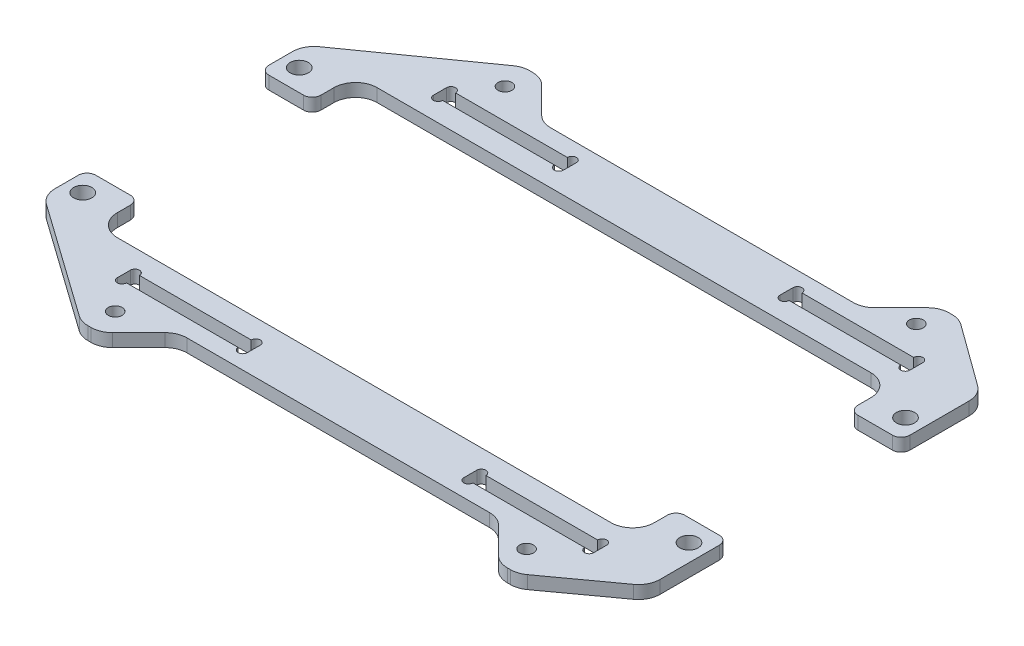
SolidWorks part; units mm, degrees
material "玻纤"
ref_plane "前视基准面" through (0, 0, 0) normal (0, 0, 1) x (1, 0, 0)
ref_plane "上视基准面" through (0, 0, 0) normal (0, 1, 0) x (1, 0, 0)
ref_plane "右视基准面" through (0, 0, 0) normal (1, 0, 0) x (0, 0, -1)
sketch "草图1" plane through (0, 0, 0) normal (0, 1, 0) x (1, 0, 0)
  line L1 (-80, -60) -> (80, -60)
  line L2 (-80, -60) -> (-80, 60)
  line L3 (-80, 60) -> (80, 60)
  line L4 (80, -60) -> (80, 60)
  line L5 (-80, -60) -> (80, 60) construction
  line L6 (-80, 60) -> (80, -60) construction
  point P0 (0, 0)
  dimension "D1" = 160
  dimension "D2" = 120
extrude "凸台-拉伸1" add sketch "草图1" along normal blind 3
sketch "草图2" plane through (0, 3, 0) normal (0, 1, 0) x (1, 0, 0)
  line L1 (-48.5, -45) -> (46.5, -45) construction
  line L2 (-48.5, -45) -> (-48.5, 45) construction
  line L3 (-48.5, 45) -> (46.5, 45) construction
  line L4 (46.5, -45) -> (46.5, 45) construction
  line L5 (-48.5, -45) -> (46.5, 45) construction
  line L6 (-48.5, 45) -> (46.5, -45) construction
  circle A0 centre (-48.5, 45) radius 1.6
  circle A1 centre (-48.5, -45) radius 1.6
  circle A2 centre (46.5, -45) radius 1.6
  circle A3 centre (46.5, 45) radius 1.6
  point P0 (-1, 0)
  dimension "D3" = 3.2
  dimension "D1" = 90
  dimension "D2" = 95
  dimension "D4" = 1
extrude "切除-拉伸1" cut sketch "草图2" against normal blind 3
sketch "草图3" plane through (0, 3, 0) normal (0, 1, 0) x (1, 0, 0)
  line L0 (80, -60) -> (80, 60) construction
  line L1 (-80, -30) -> (80, -30)
  line L2 (-80, -30) -> (-80, 30)
  line L3 (-80, 30) -> (80, 30)
  line L4 (80, -30) -> (80, 30)
  line L5 (-80, -30) -> (80, 30) construction
  line L6 (-80, 30) -> (80, -30) construction
  line L7 (-80, 30) -> (-44.2474, 60)
  line L8 (80, 60) -> (-80, 60) construction
  line L9 (-44.2474, 60) -> (44.2474, 60)
  line L10 (44.2474, 60) -> (80, 30)
  line L11 (80, -30) -> (44.2474, -60)
  line L12 (-80, -60) -> (80, -60) construction
  line L13 (44.2474, -60) -> (-44.2474, -60)
  line L14 (-44.2474, -60) -> (-80, -30)
  point P0 (0, 0)
  line M11 (80, -60) -> (80, 60)
  line M12 (80, 60) -> (-80, 60)
  line M13 (-80, 60) -> (-80, -60)
  line M14 (-80, -60) -> (80, -60)
  dimension "D1" = 60
  dimension "D2" = 40
  dimension "D3" = 40
extrude "切除-拉伸2" cut sketch "草图3" against normal blind 3 contours L7 M13 M12 | L10 M12 M11 | L11 M11 M14 | L14 M14 M13
sketch "草图14" plane through (0, 3, 0) normal (0, 1, 0) x (1, 0, 0)
  line L0 (44.2474, 60) -> (80, 30) construction
  line L1 (68, 40.0692) -> (80, 40.0692)
  line L2 (68, 40.0692) -> (68, -40.0692)
  line L3 (68, -40.0692) -> (80, -40.0692)
  line L4 (80, 40.0692) -> (80, -40.0692)
  line L5 (80, -30) -> (44.2474, -60) construction
  dimension "D1" = 12
extrude "切除-拉伸13" cut sketch "草图14" against normal through all
sketch "草图4" plane through (0, 3, 0) normal (0, 1, 0) x (1, 0, 0)
  line L0 (-76, -30) -> (-76, 30) construction
  line L1 (-80, 30) -> (-72, 30) construction
  line L2 (-80, 30) -> (-80, -30) construction
  line L3 (-80, -30) -> (-72, -30) construction
  line L4 (-72, 30) -> (-72, -30) construction
  line L5 (0, -60) -> (0, 60) construction
  line L6 (-44.2474, -60) -> (44.2474, -60) construction
  line L7 (44.2474, 60) -> (-44.2474, 60) construction
  line L8 (-76, 25) -> (64, 25) construction
  line L9 (64, 25) -> (64, -25) construction
  line L10 (-76, -25) -> (64, -25) construction
  line L11 (68, 40.0692) -> (68, -40.0692) construction
  line L13 (64, 0) -> (-76, 0) construction
  circle A0 centre (-76, 25) radius 2.1
  circle A1 centre (-76, -25) radius 2.1
  circle A2 centre (-76, 0) radius 2.1
  circle A8 centre (64, 25) radius 2.1
  circle A9 centre (64, -25) radius 2.1
  circle A11 centre (64, 0) radius 2.1
  point P15 (-76, 0)
  dimension "D3" = 5
  dimension "D5" = 5
  dimension "D6" = 4.2
  dimension "D8" = 4.2
  dimension "D1" = 8
  dimension "D7" = 4
extrude "切除-拉伸3" cut sketch "草图4" against normal blind 8
sketch "草图5" plane through (0, 3, 0) normal (0, 1, 0) x (1, 0, 0)
  line L0 (-44.2474, -60) -> (44.2474, -60) construction
  line L1 (-80, 35) -> (68, 35) construction
  line L2 (-80, 35) -> (-80, -35) construction
  line L3 (-80, -35) -> (68, -35) construction
  line L5 (-55, 35) -> (-25, 35)
  line L6 (-55, 35) -> (-55, 38)
  line L7 (-55, 38) -> (-25, 38)
  line L8 (-25, 35) -> (-25, 38)
  line L9 (25, 35) -> (55, 35)
  line L10 (25, 35) -> (25, 38)
  line L11 (25, 38) -> (55, 38)
  line L12 (55, 35) -> (55, 38)
  line L13 (-55, -35) -> (-25, -35)
  line L14 (-55, -35) -> (-55, -38)
  line L15 (-55, -38) -> (-25, -38)
  line L16 (-25, -35) -> (-25, -38)
  line L17 (25, -35) -> (55, -35)
  line L18 (25, -35) -> (25, -38)
  line L19 (25, -38) -> (55, -38)
  line L20 (55, -35) -> (55, -38)
  line L21 (44.2474, 60) -> (-44.2474, 60) construction
  line L23 (68, 40.0692) -> (68, -40.0692) construction
  dimension "D1" = 3
  dimension "D2" = 3
  dimension "D3" = 3
  dimension "D4" = 3
  dimension "D5" = 25
  dimension "D6" = 30
  dimension "D7" = 30
  dimension "D8" = 13
  dimension "D10" = 30
  dimension "D11" = 30
  dimension "D12" = 25
  dimension "D13" = 25
  dimension "D15" = 25
extrude "切除-拉伸4" cut sketch "草图5" against normal blind 8
sketch "草图7" plane through (0, 3, 0) normal (0, 1, 0) x (1, 0, 0)
  line L0 (-80, -30) -> (-50.4129, -51)
  line L1 (-50.4129, -51) -> (-46.0147, -51)
  line L2 (-46.0147, -51) -> (-37.0147, -42)
  line L3 (-37.0147, -42) -> (37.0147, -42)
  line L4 (0, 60) -> (0, -60) construction
  line L5 (44.2474, 60) -> (-44.2474, 60) construction
  line L6 (-80, 0) -> (68, 0) construction
  line L7 (-80, 30) -> (-80, -30) construction
  line L8 (-44.2474, -60) -> (44.2474, -60) construction
  line L14 (-67, -29) -> (67, 29) construction
  line L15 (-67, 29) -> (67, -29) construction
  line L21 (-55, -38) -> (-25, -38) construction
  line L22 (68, -40.0692) -> (44.2474, -60) construction
  line L23 (-44.2474, -60) -> (-80, -30) construction
  line L24 (68, -40.0692) -> (44.2474, -60)
  line L25 (68, 40.0692) -> (68, -40.0692) construction
  line L29 (-44.2474, -60) -> (44.2474, -60)
  line L30 (-44.2474, -60) -> (-80, -30)
  line L31 (46.0147, -51) -> (37.0147, -42)
  line L32 (50.4129, -51) -> (46.0147, -51)
  line L34 (68, -38.2242) -> (50.4129, -51)
  line L35 (68, -40.0692) -> (68, -38.2242)
  line L36 (68, 40.0692) -> (68, 38.2242)
  line L37 (68, 40.0692) -> (44.2474, 60)
  line L38 (-44.2474, 60) -> (44.2474, 60)
  line L39 (-44.2474, 60) -> (-80, 30)
  line L40 (-80, 30) -> (-50.4129, 51)
  line L41 (-50.4129, 51) -> (-46.0147, 51)
  line L42 (-46.0147, 51) -> (-37.0147, 42)
  line L43 (-37.0147, 42) -> (37.0147, 42)
  line L44 (46.0147, 51) -> (37.0147, 42)
  line L45 (50.4129, 51) -> (46.0147, 51)
  line L46 (68, 38.2242) -> (50.4129, 51)
  circle A6 centre (-48.5, -45) radius 1.6 construction
  point P17 (0, 0)
  dimension "D1" = 6
  dimension "D7" = 6
  dimension "D6" = 58
  dimension "D8" = 6
  dimension "D9" = 135
  dimension "D10" = 4
  dimension "D11" = 1.845
extrude "切除-拉伸7" cut sketch "草图7" against normal blind 5
fillet "圆角2" radius 5 16 edges at (68, 1.5, 38.2242) (50.4129, 1.5, 51) (46.0147, 1.5, 51) (37.0147, 1.5, 42) (-37.0147, 1.5, 42) (-46.0147, 1.5, 51) (-50.4129, 1.5, 51) (-80, 1.5, 30) (-80, 1.5, -30) (68, 1.5, -38.2242) (50.4129, 1.5, -51) (46.0147, 1.5, -51) (37.0147, 1.5, -42) (-37.0147, 1.5, -42) (-50.4129, 1.5, -51) (-46.0147, 1.5, -51)
sketch "草图11" plane through (0, 3, 0) normal (0, 1, 0) x (1, 0, 0)
  line L0 (-25, 38) -> (-55, 38) construction
  line L1 (-25, 35) -> (-25, 38) construction
  line L2 (-55, 35) -> (-25, 35) construction
  line L3 (-55, 38) -> (-55, 35) construction
  line L4 (-25, 35) -> (25, 35) construction
  line L5 (-25, -35) -> (25, -35) construction
  line L6 (0, 35) -> (0, -35) construction
  line L7 (25, 35) -> (25, -35) construction
  line L8 (0, 0) -> (25, 0) construction
  circle A0 centre (-53.95, 38) radius 1.05
  circle A1 centre (-53.95, 35) radius 1.05
  circle A2 centre (-26.05, 35) radius 1.05
  circle A3 centre (-26.05, 38) radius 1.05
  circle A16 centre (26.05, 38) radius 1.05
  circle A17 centre (26.05, 35) radius 1.05
  circle A18 centre (53.95, 35) radius 1.05
  circle A19 centre (53.95, 38) radius 1.05
  circle A20 centre (53.95, -38) radius 1.05
  circle A21 centre (53.95, -35) radius 1.05
  circle A22 centre (26.05, -35) radius 1.05
  circle A23 centre (26.05, -38) radius 1.05
  circle A24 centre (-26.05, -38) radius 1.05
  circle A25 centre (-26.05, -35) radius 1.05
  circle A26 centre (-53.95, -35) radius 1.05
  circle A27 centre (-53.95, -38) radius 1.05
  dimension "D1" = 2.1
extrude "切除-拉伸10" cut sketch "草图11" against normal blind 10
sketch "草图13" plane through (0, 3, 0) normal (0, 1, 0) x (1, 0, 0)
  line L1 (-8.6603, 0) -> (-4.3301, -7.5)
  line L2 (-4.3301, -7.5) -> (4.3301, -7.5)
  line L3 (4.3301, -7.5) -> (8.6603, 0)
  line L4 (8.6603, 0) -> (4.3301, 7.5)
  line L5 (4.3301, 7.5) -> (-4.3301, 7.5)
  line L6 (-4.3301, 7.5) -> (-8.6603, 0)
  circle A0 centre (0, 0) radius 7.5 construction
  dimension "D1" = 15
extrude "切除-拉伸12" cut sketch "草图13" against normal blind 10
sketch "草图15" plane through (0, 3, 0) normal (0, 1, 0) x (1, 0, 0)
  line L0 (-52.9, 35) -> (-27.1, 35) construction
  line L1 (-63, 30) -> (51, 30)
  line L2 (-68, 25) -> (-68, -25)
  line L3 (-63, -30) -> (51, -30)
  line L4 (56, 25) -> (56, -25)
  line L5 (-27.1, -35) -> (-52.9, -35) construction
  circle A0 centre (-76, 25) radius 2.1 construction
  circle A1 centre (64, 25) radius 2.1 construction
  arc A2 (-68, -25) -> (-63, -30) centre (-63, -25) ccw
  arc A3 (51, -30) -> (56, -25) centre (51, -25) ccw
  arc A4 (51, 30) -> (56, 25) centre (51, 25) cw
  arc A5 (-63, 30) -> (-68, 25) centre (-63, 25) ccw
  dimension "D5" = 5
  dimension "D1" = 5
  dimension "D2" = 5
  dimension "D3" = 8
  dimension "D4" = 8
extrude "切除-拉伸14" cut sketch "草图15" against normal through all
sketch "草图16" plane through (0, 3, 0) normal (0, 1, 0) x (1, 0, 0)
  line L0 (-80, 27.4174) -> (-80, -27.4174) construction
  line L1 (-80, 20) -> (68, 20)
  line L2 (-80, 20) -> (-80, -20)
  line L3 (-80, -20) -> (68, -20)
  line L4 (68, 20) -> (68, -20)
  line L5 (68, 35.6763) -> (68, -35.6763) construction
  circle A0 centre (-76, -25) radius 2.1 construction
  circle A1 centre (-76, 25) radius 2.1 construction
  dimension "D1" = 5
  dimension "D2" = 5
extrude "切除-拉伸15" cut sketch "草图16" against normal through all
fillet "圆角3" radius 2 4 edges at (68, 1.5, -20) (56, 1.5, -20) (-68, 1.5, -20) (-80, 1.5, -20)
fillet "圆角4" radius 2 4 edges at (56, 1.5, 20) (68, 1.5, 20) (-68, 1.5, 20) (-80, 1.5, 20)
